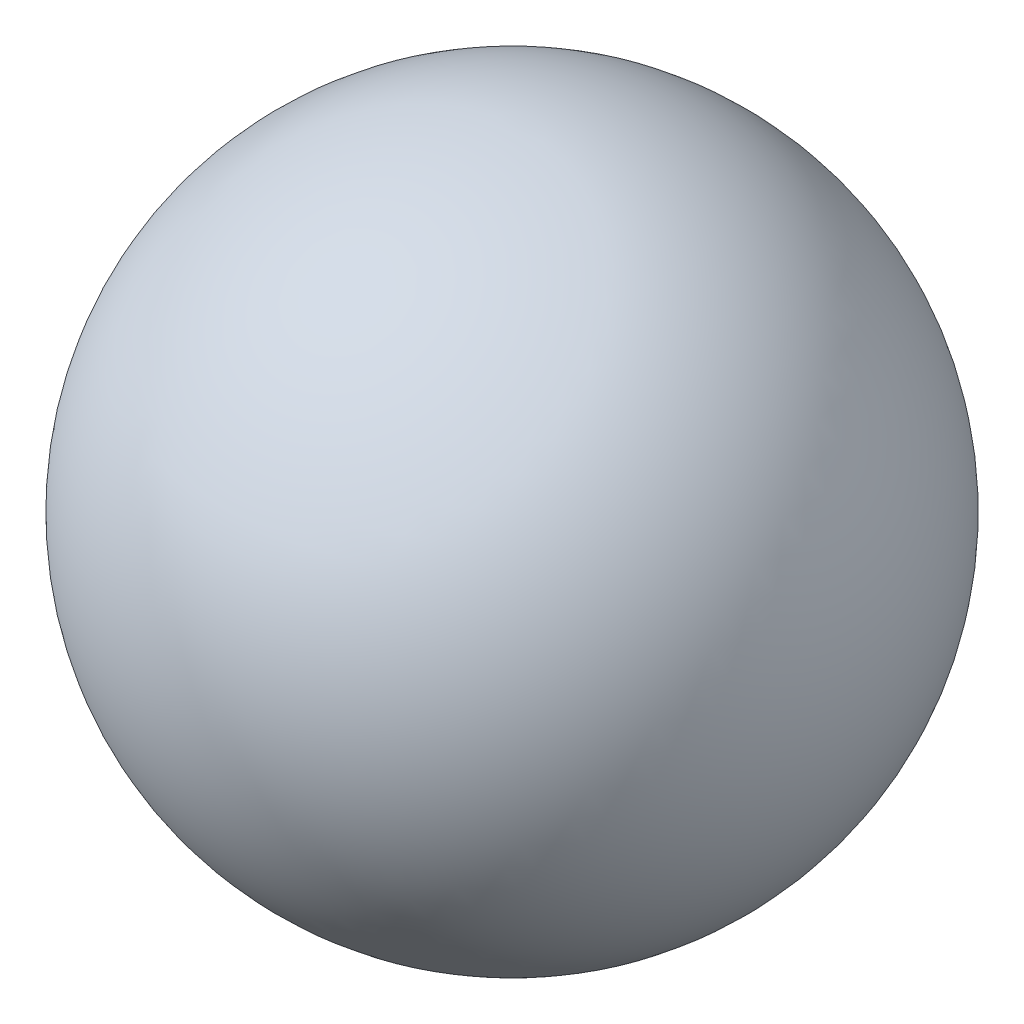
SolidWorks part; units mm, degrees
ref_plane "Front Plane" through (0, 0, 0) normal (0, 0, 1) x (1, 0, 0)
ref_plane "Top Plane" through (0, 0, 0) normal (0, 1, 0) x (1, 0, 0)
ref_plane "Right Plane" through (0, 0, 0) normal (1, 0, 0) x (0, 0, -1)
sketch "Sketch1" plane through (0, 0, 0) normal (0, 0, 1) x (1, 0, 0)
  line L0 (0, 21) -> (0, -21)
  arc A0 (0, 21) -> (0, -21) centre (0, 0) cw
  point P3 (0, 0)
  point P5 (0, 0)
  dimension "D1" = 42
revolve "Revolve1" add sketch "Sketch1" angle 360 about L0
